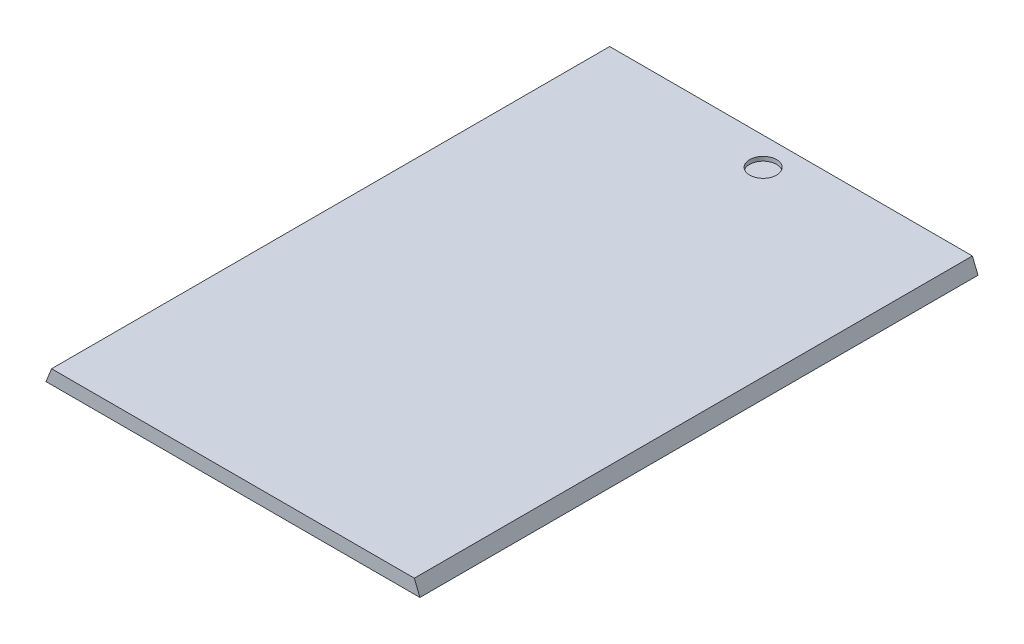
SolidWorks part; units mm, degrees
ref_plane "Front Plane" through (0, 0, 0) normal (0, 0, 1) x (1, 0, 0)
ref_plane "Top Plane" through (0, 0, 0) normal (0, 1, 0) x (1, 0, 0)
ref_plane "Right Plane" through (0, 0, 0) normal (1, 0, 0) x (0, 0, -1)
sketch "Sketch1" plane through (0, 0, 0) normal (0, 0, 1) x (1, 0, 0)
  line L1 (-106.5, 28.3022) -> (23.5, 28.3022)
  line L3 (-108.5, 23.3022) -> (25.5, 23.3022)
  line L5 (-108.5, 23.3022) -> (-106.5, 28.3022)
  line L8 (23.5, 28.3022) -> (25.5, 23.3022)
  dimension "D1" = 5
  dimension "D2" = 134
  dimension "D3" = 2
  dimension "D4" = 2
extrude "Boss-Extrude1" add sketch "Sketch1" along normal blind 200
sketch "Sketch2" plane through (0, 28.3022, 0) normal (0, 1, 0) x (1, 0, 0)
  line L2 (-41.5, 0) -> (-41.5, -200) construction
  line L3 (23.5, 0) -> (-106.5, 0) construction
  line L4 (23.5, -200) -> (-106.5, -200) construction
  circle A0 centre (-41.5, -10) radius 4.8282
  dimension "D1" = 0
  dimension "D2" = 10
extrude "Cut-Extrude1" cut sketch "Sketch2" against normal blind 1.5
equation "\"Module Width\"= 75mm"
equation "\"Module length\"= 150mm"
equation "\"Wall Thickness\"= 5mm"
equation "\"Lid lenght\"= \"Module length\" + \"Wall Thickness\" * 2 + 40"
equation "\"Lid width\" = \"Module Width\" + \"Wall Thickness\" * 3 + 50 - 6"
equation "\"D1@Boss-Extrude1\"=\"Lid lenght\""
equation "\"D2@Sketch1\"=\"Lid width\""
equation "\"Top Lid\"= \"Lid width\" - 4"
